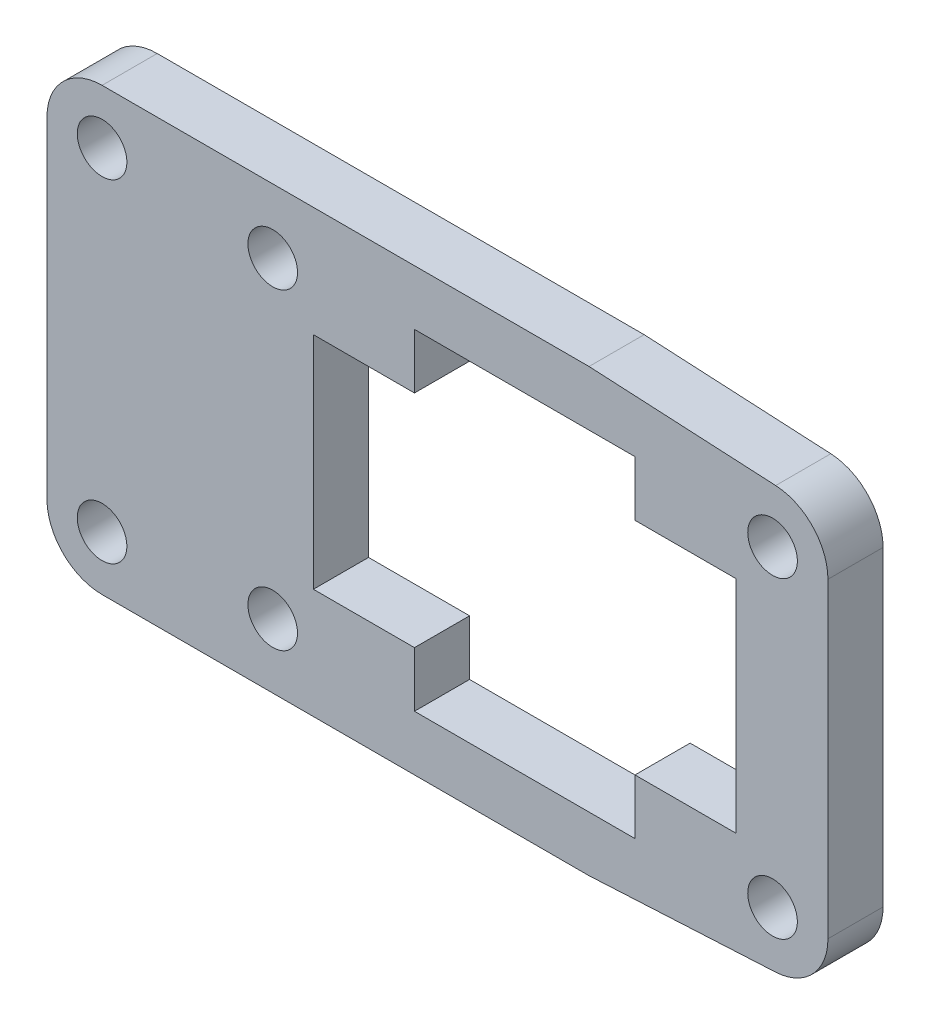
SolidWorks part; units mm, degrees
ref_plane "前视基准面" through (0, 0, 0) normal (0, 0, 1) x (1, 0, 0)
ref_plane "上视基准面" through (0, 0, 0) normal (0, 1, 0) x (1, 0, 0)
ref_plane "右视基准面" through (0, 0, 0) normal (1, 0, 0) x (0, 0, -1)
ref_plane "基准面1" through (0, 0, 3) normal (0, 0, 1) x (1, 0, 0)
sketch "草图1" plane through (0, 0, 3) normal (0, 0, 1) x (1, 0, 0)
  line L0 (4.3434, 17.9998) -> (4.3434, 20.9998)
  line L1 (4.3434, 20.9998) -> (16.3434, 20.9998)
  line L2 (16.3434, 20.9998) -> (16.3434, 17.9998)
  line L3 (16.3434, 17.9998) -> (21.8432, 17.9998)
  line L4 (21.8432, 17.9998) -> (21.8432, 6)
  line L5 (21.8432, 6) -> (16.3434, 6)
  line L6 (16.3434, 6) -> (16.3434, 3)
  line L7 (16.3434, 3) -> (4.3434, 3)
  line L8 (4.3434, 3) -> (4.3434, 6)
  line L9 (4.3434, 6) -> (-1.1565, 6)
  line L10 (-1.1565, 6) -> (-1.1565, 17.9998)
  line L11 (-1.1565, 17.9998) -> (4.3434, 17.9998)
  line L12 (-15.6573, 20.9998) -> (-15.6573, 3)
  line L13 (-12.6573, 0) -> (13.8437, 0)
  line L14 (13.8437, 0) -> (24.0014, 0.533)
  line L15 (26.8442, 3.5289) -> (26.8442, 20.4719)
  line L16 (24.0011, 23.4678) -> (13.8437, 23.9998)
  line L17 (13.8437, 23.9998) -> (-12.6573, 23.9998)
  circle A0 centre (-3.3701, 3.5011) radius 1.35
  circle A1 centre (-3.3701, 20.4984) radius 1.35
  circle A2 centre (23.83, 3.5011) radius 1.35
  circle A3 centre (23.83, 20.4984) radius 1.35
  circle A4 centre (-12.6575, 21.049) radius 1.35
  circle A5 centre (-12.6575, 2.95) radius 1.35
  arc A6 (-15.6573, 3) -> (-12.6573, 0) centre (-12.6573, 3) ccw
  arc A7 (24.0014, 0.533) -> (26.8442, 3.5289) centre (23.8442, 3.5289) ccw
  arc A8 (26.8442, 20.4719) -> (24.0011, 23.4678) centre (23.8442, 20.4719) ccw
  arc A9 (-12.6573, 23.9998) -> (-15.6573, 20.9998) centre (-12.6573, 20.9998) ccw
extrude "凸台-拉伸1" add sketch "草图1" against normal blind 3
